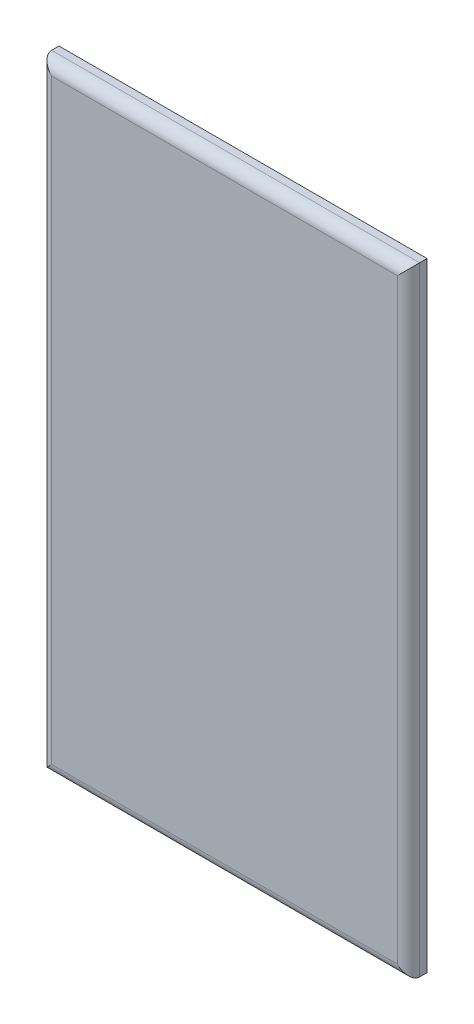
SolidWorks part; units mm, degrees
ref_plane "Plano frontal" through (0, 0, 0) normal (0, 0, 1) x (1, 0, 0)
ref_plane "Plano superior" through (0, 0, 0) normal (0, 1, 0) x (1, 0, 0)
ref_plane "Plano direito" through (0, 0, 0) normal (1, 0, 0) x (0, 0, -1)
sketch "Esboço1" plane through (0, 0, 0) normal (0, 0, 1) x (1, 0, 0)
  line L1 (-44.0525, 94.6578) -> (55.0475, 94.6578)
  line L2 (-44.0525, 94.6578) -> (-44.0525, -71.8622)
  line L3 (-44.0525, -71.8622) -> (55.0475, -71.8622)
  line L4 (55.0475, 94.6578) -> (55.0475, -71.8622)
extrude "Ressalto-extrusão1" add sketch "Esboço1" along normal blind 5
fillet "Filete1" radius 3 4 edges at (5.4975, -71.8622, 5) (55.0475, 11.3978, 5) (5.4975, 94.6578, 5) (-44.0525, 11.3978, 5)
sketch "Esboço2" plane through (0, 0, 0) normal (0, 0, -1) x (-1, 0, 0)
  line L0 (-55.0475, 94.6578) -> (44.0525, 94.6578) construction
  line L2 (-55.0475, -71.8622) -> (-55.0475, 94.6578) construction
  circle A0 centre (-51.4975, 91.1078) radius 3.1
  point P6 (-55.0475, 91.0906)
  dimension "D1" = 3.55
  dimension "D2" = 3.55
extrude "Corte-extrusão1" cut sketch "Esboço2" against normal blind 1.6
sketch "Esboço3" plane through (0, 0, 0) normal (0, 0, -1) x (-1, 0, 0)
  line L0 (44.0525, 94.6578) -> (44.0525, -71.8622) construction
  line L1 (-55.0475, 94.6578) -> (44.0525, 94.6578) construction
  circle A0 centre (40.5025, 91.1078) radius 3.1
  dimension "D1" = 3.55
  dimension "D2" = 3.55
extrude "Corte-extrusão2" cut sketch "Esboço3" against normal blind 1.6
sketch "Esboço4" plane through (0, 0, 0) normal (0, 0, -1) x (-1, 0, 0)
  line L0 (44.0525, -71.8622) -> (-55.0475, -71.8622) construction
  line L1 (-55.0475, -71.8622) -> (-55.0475, 94.6578) construction
  circle A0 centre (-51.4975, -68.3122) radius 3.1
  dimension "D1" = 3.55
  dimension "D2" = 3.55
extrude "Corte-extrusão3" cut sketch "Esboço4" against normal blind 1.6
sketch "Esboço5" plane through (0, 0, 0) normal (0, 0, -1) x (-1, 0, 0)
  line L0 (44.0525, 94.6578) -> (44.0525, -71.8622) construction
  line L1 (44.0525, -71.8622) -> (-55.0475, -71.8622) construction
  circle A0 centre (40.5025, -68.3122) radius 3.1
  dimension "D1" = 3.55
  dimension "D2" = 3.55
extrude "Corte-extrusão4" cut sketch "Esboço5" against normal blind 1.6 contours A0
